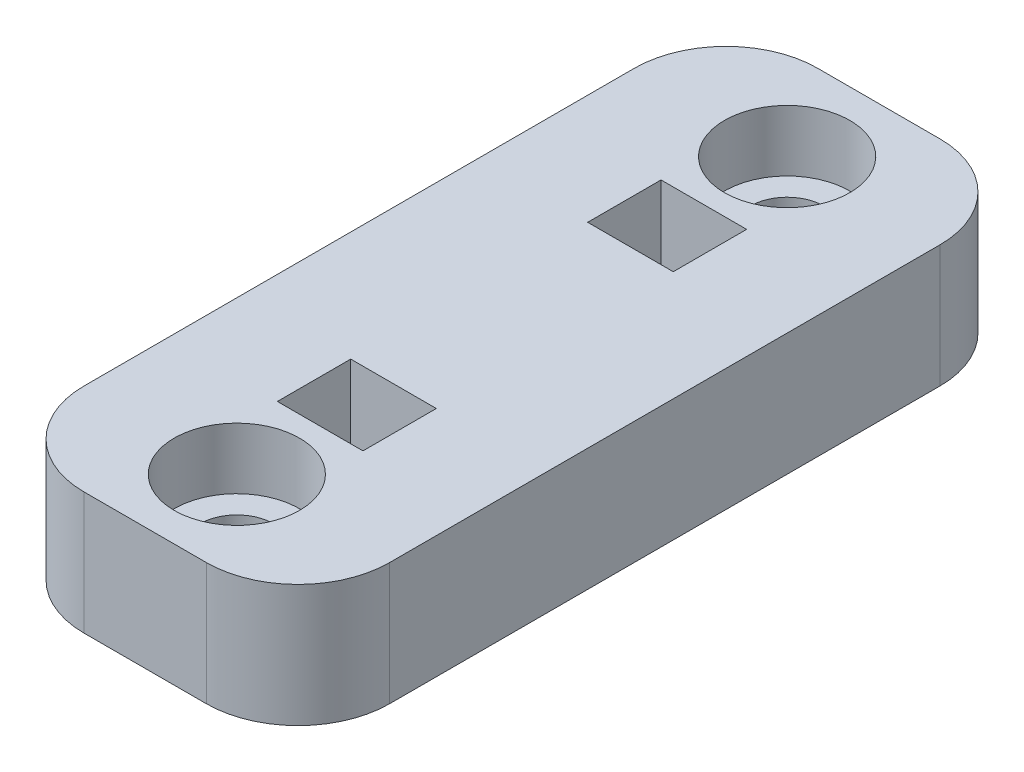
SolidWorks part; units mm, degrees
ref_plane "Front Plane" through (0, 0, 0) normal (0, 0, 1) x (1, 0, 0)
ref_plane "Top Plane" through (0, 0, 0) normal (0, 1, 0) x (1, 0, 0)
ref_plane "Right Plane" through (0, 0, 0) normal (1, 0, 0) x (0, 0, -1)
sketch "Sketch1" plane through (0, 0, 0) normal (0, 1, 0) x (1, 0, 0)
  line L0 (5, 5.725) -> (5, 0) construction
  line L1 (0, 0) -> (10, 0)
  line L2 (0, 0) -> (0, 24)
  line L3 (0, 24) -> (10, 24)
  line L4 (10, 0) -> (10, 24)
  line L5 (3.6, 18.275) -> (6.4, 18.275)
  line L6 (3.6, 18.275) -> (3.6, 15.875)
  line L7 (3.6, 15.875) -> (6.4, 15.875)
  line L8 (6.4, 18.275) -> (6.4, 15.875)
  line L9 (3.6, 8.125) -> (6.4, 8.125)
  line L10 (3.6, 8.125) -> (3.6, 5.725)
  line L11 (3.6, 5.725) -> (6.4, 5.725)
  line L12 (6.4, 8.125) -> (6.4, 5.725)
  line L13 (5, 18.275) -> (5, 24) construction
  line L14 (5, 15.875) -> (5, 8.125) construction
  line L15 (0, 12) -> (10, 12) construction
  circle A0 centre (5, 21) radius 1.2
  circle A1 centre (5, 3) radius 1.2
  point P26 (5, 12)
  dimension "D8" = 2.4
  dimension "D1" = 2.8
  dimension "D2" = 10
  dimension "D3" = 2.4
  dimension "D4" = 7.75
  dimension "D5" = 18
  dimension "D6" = 3
  dimension "D7" = 3
extrude "Boss-Extrude1" add sketch "Sketch1" along normal blind 4
fillet "Fillet1" radius 3 4 edges at (0, 2, -24) (10, 2, -24) (10, 2, 0) (0, 2, 0)
sketch "Sketch2" plane through (0, 4, 0) normal (0, 1, 0) x (1, 0, 0)
  circle A0 centre (5, 3) radius 2.05
  circle A1 centre (5, 21) radius 2.05
  dimension "D1" = 4.1
extrude "Cut-Extrude1" cut sketch "Sketch2" against normal blind 2
